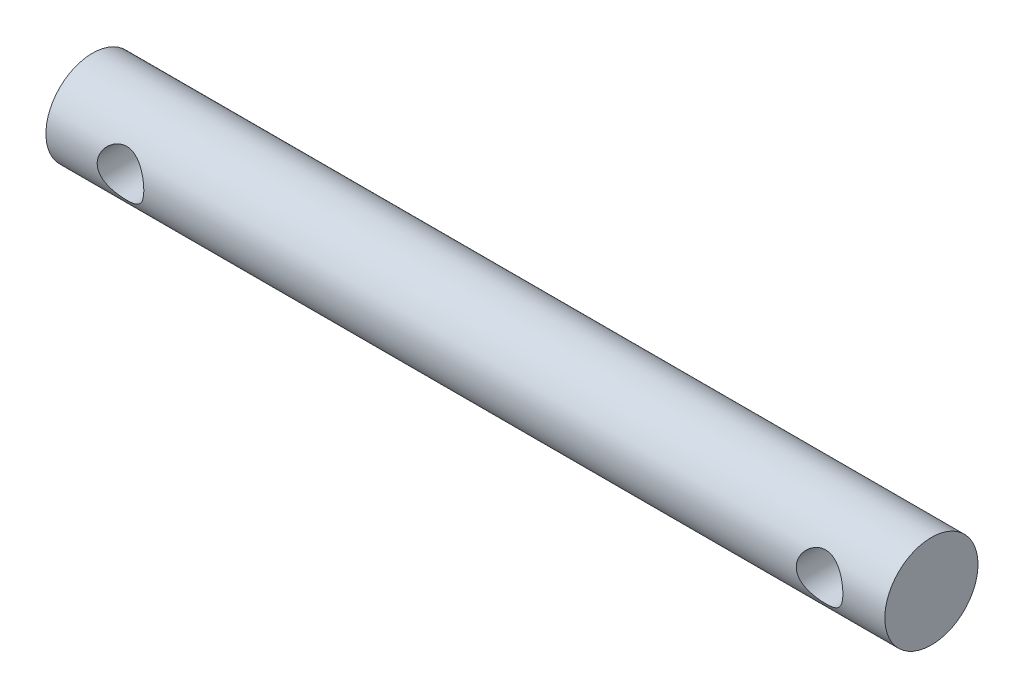
SolidWorks part; units mm, degrees
ref_plane "Front Plane" through (0, 0, 0) normal (0, 0, 1) x (1, 0, 0)
ref_plane "Top Plane" through (0, 0, 0) normal (0, 1, 0) x (1, 0, 0)
ref_plane "Right Plane" through (0, 0, 0) normal (1, 0, 0) x (0, 0, -1)
sketch "Sketch1" plane through (0, 0, 0) normal (1, 0, 0) x (0, 0, -1)
  circle A0 centre (0, 0) radius 2.5
  dimension "D1" = 5
extrude "Boss-Extrude1" add sketch "Sketch1" against normal blind 45
sketch "Sketch3" plane through (0, 0, 0) normal (0, 0, 1) x (1, 0, 0)
  line L0 (-45, 2.5) -> (-45, -2.5) construction
  line L1 (0, -2.5) -> (0, 2.5) construction
  circle A0 centre (-41, 0) radius 1.25
  circle A1 centre (-3.5, 0) radius 1.25
  dimension "D1" = 4
  dimension "D3" = 2.5
  dimension "D2" = 3.5
extrude "Cut-Extrude1" cut sketch "Sketch3" against normal through all both and the other way through all
